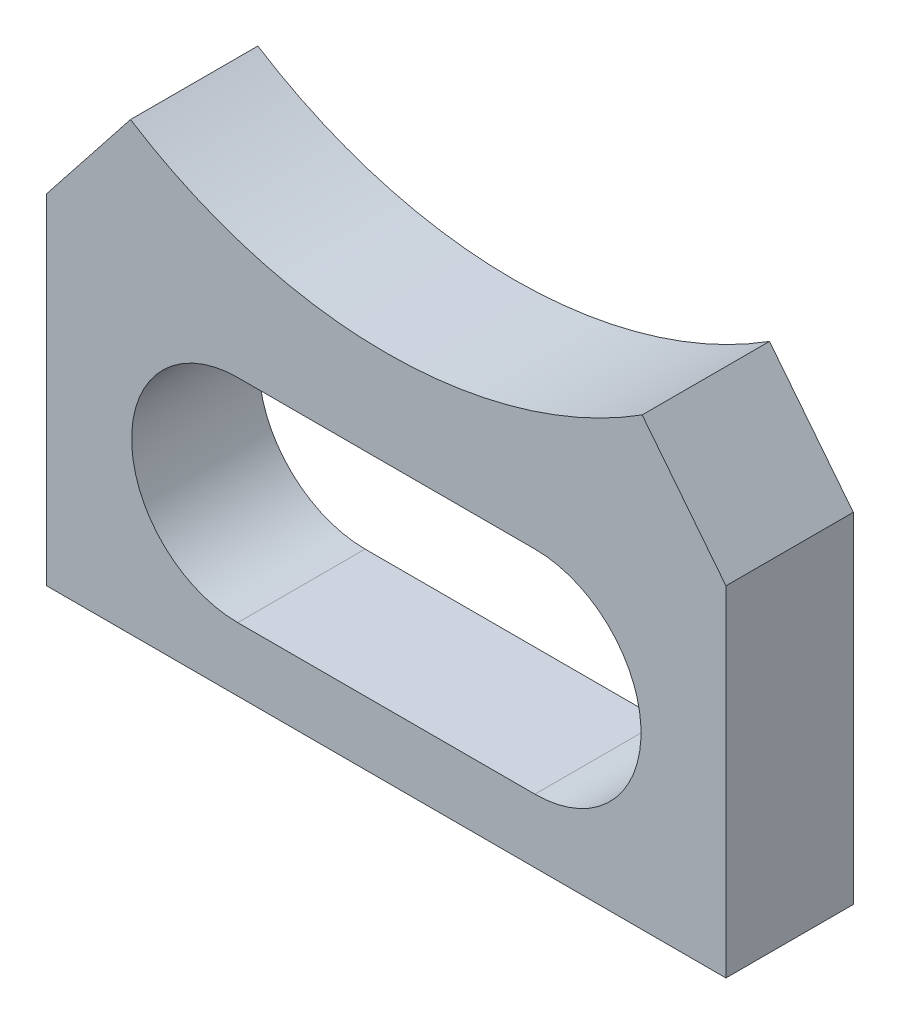
SolidWorks part; units mm, degrees
ref_plane "Plan de face" through (0, 0, 0) normal (0, 0, 1) x (1, 0, 0)
ref_plane "Plan de dessus" through (0, 0, 0) normal (0, 1, 0) x (1, 0, 0)
ref_plane "Plan de droite" through (0, 0, 0) normal (1, 0, 0) x (0, 0, -1)
sketch "Esquisse1" plane through (0, 0, 0) normal (0, 0, 1) x (1, 0, 0)
  line L0 (-16, 0) -> (16, 0)
  line L1 (-16, 0) -> (-16, 16)
  line L2 (0, 21) -> (12.052, 21) construction
  line L3 (16, 16) -> (16, 0)
  line L4 (-16, 16) -> (-12.052, 21)
  line L6 (-12.052, 21) -> (-16, 21) construction
  line L7 (12.052, 21) -> (16, 21) construction
  line L8 (0, 74.4173) -> (0, 62.5) construction
  line L10 (16, 16) -> (12.052, 21)
  line L11 (0, 62.5) -> (0, 21) construction
  line L12 (0, 21) -> (0, -33.4261) construction
  line L13 (-12.052, 21) -> (0, 21) construction
  line L14 (-7, 8) -> (7, 8) construction
  line L15 (-7, 13) -> (7, 13)
  line L16 (-7, 3) -> (7, 3)
  arc A0 (-12.052, 21) -> (12.052, 21) centre (0, 40) ccw
  arc A1 (0, 62.5) -> (-12.052, 21) centre (0, 40) ccw construction
  arc A2 (12.052, 21) -> (0, 62.5) centre (0, 40) ccw construction
  arc A3 (-7, 13) -> (-7, 3) centre (-7, 8) ccw
  arc A4 (7, 3) -> (7, 13) centre (7, 8) ccw
  point P14 (0, 17.5)
  point P17 (0, 8)
  dimension "D2" = 45
  dimension "D8" = 5
  dimension "D1" = 32
  dimension "D3" = 16
  dimension "D4" = 21
  dimension "D5" = 17.5
  dimension "D6" = 9
  dimension "D7" = 8
extrude "Boss.-Extru.2" add sketch "Esquisse1" against normal blind 6
